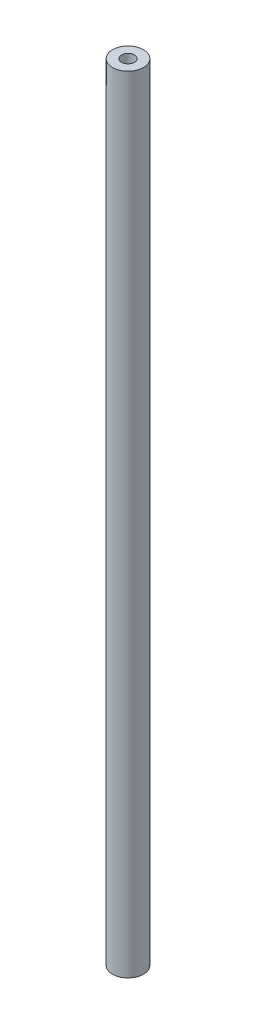
SolidWorks part; units mm, degrees
ref_plane "Front Plane" through (0, 0, 0) normal (0, 0, 1) x (1, 0, 0)
ref_plane "Top Plane" through (0, 0, 0) normal (0, 1, 0) x (1, 0, 0)
ref_plane "Right Plane" through (0, 0, 0) normal (1, 0, 0) x (0, 0, -1)
sketch "Sketch1" plane through (0, 0, 0) normal (0, 1, 0) x (1, 0, 0)
  circle A0 centre (0, 0) radius 6
  circle A1 centre (0, 0) radius 2.5
  dimension "D1" = 12
  dimension "D2" = 5
extrude "Boss-Extrude1" add sketch "Sketch1" along normal mid plane 304.8
